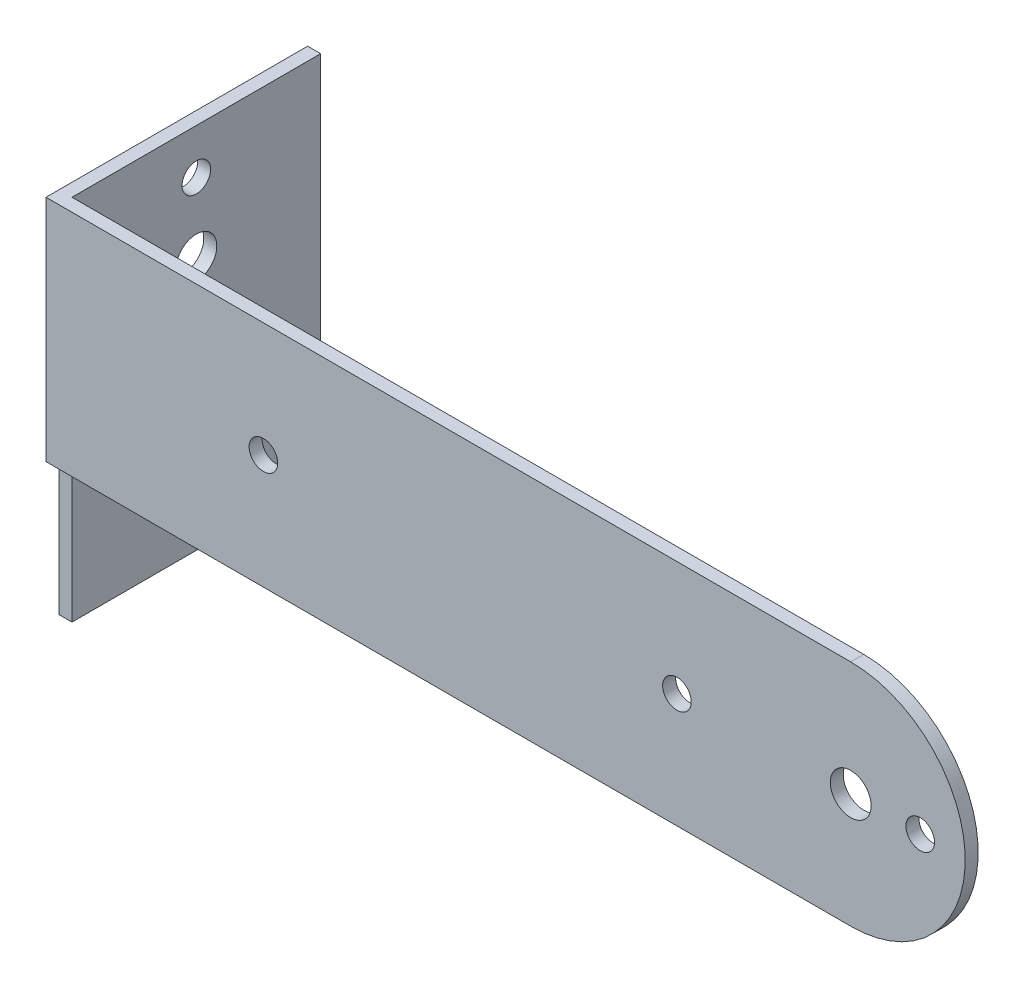
SolidWorks part; units mm, degrees
material "6061 Alloy"
ref_plane "Front Plane" through (0, 0, 0) normal (0, 0, 1) x (1, 0, 0)
ref_plane "Top Plane" through (0, 0, 0) normal (0, 1, 0) x (1, 0, 0)
ref_plane "Right Plane" through (0, 0, 0) normal (1, 0, 0) x (0, 0, -1)
sketch "Sketch1" plane through (0, 0, 0) normal (0, 0, 1) x (1, 0, 0)
  line L0 (0, 14) -> (-98.41, 14)
  line L1 (-98.41, 14) -> (-98.41, -14)
  line L2 (-98.41, -14) -> (0, -14)
  arc A0 (0, -14) -> (0, 14) centre (0, 0) ccw
  dimension "D1" = 28
  dimension "D2" = 98.41
extrude "Boss-Extrude1" add sketch "Sketch1" along normal blind 1.59
sketch "Sketch2" plane through (0, 0, 0) normal (0, 0, -1) x (-1, 0, 0)
  line L1 (98.41, 14) -> (96.82, 14)
  line L2 (98.41, 14) -> (98.41, -31)
  line L3 (98.41, -31) -> (96.82, -31)
  line L4 (96.82, 14) -> (96.82, -31)
  point P5 (97.615, -31)
  point P6 (98.41, -8.5)
  dimension "D1" = 45
  dimension "D2" = 1.59
extrude "Boss-Extrude2" add sketch "Sketch2" along normal blind 30.41
sketch "Sketch3" plane through (0, 0, 0) normal (0, 0, -1) x (-1, 0, 0)
  line L0 (-40.1644, 0) -> (163.0587, 0) construction
  line L1 (96.82, 14) -> (96.82, -14) construction
  circle A0 centre (71.82, 0) radius 1.75
  circle A3 centre (-8.5, 0) radius 1.75
  circle A4 centre (0, 0) radius 2.5
  circle A5 centre (21.25, 0) radius 1.75
  dimension "D6" = 5
  dimension "D3" = 3.5
  dimension "D1" = 8.5
  dimension "D2" = 29.75
  dimension "D5" = 25
extrude "Cut-Extrude1" cut sketch "Sketch3" against normal through all
sketch "Sketch4" plane through (-98.41, 0, 0) normal (-1, 0, 0) x (0, 0, 1)
  line L0 (-15.205, 26.9729) -> (-15.205, -41.0088) construction
  line L1 (-30.41, -31) -> (-30.41, 14) construction
  circle A0 centre (-15.205, 0) radius 2.5
  circle A1 centre (-15.205, 8.5) radius 1.75
  circle A2 centre (-15.205, -21.25) radius 1.75
  dimension "D4" = 3.5
  dimension "D5" = 5
  dimension "D1" = 15.205
  dimension "D2" = 8.5
  dimension "D3" = 29.75
extrude "Cut-Extrude2" cut sketch "Sketch4" against normal blind 30.41
